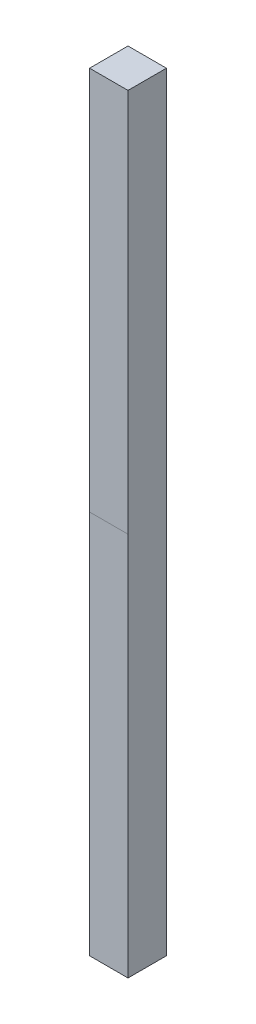
SolidWorks part; units mm, degrees
ref_plane "Front" through (0, 0, 0) normal (0, 0, 1) x (1, 0, 0)
ref_plane "Top" through (0, 0, 0) normal (0, 1, 0) x (1, 0, 0)
ref_plane "Right" through (0, 0, 0) normal (1, 0, 0) x (0, 0, -1)
other "Configuration Table"
sketch "Sketch1" plane through (0, 0, 0) normal (0, 1, 0) x (1, 0, 0)
  line L1 (0, 0) -> (25.4, 0)
  line L2 (0, 0) -> (0, 25.4)
  line L3 (0, 25.4) -> (25.4, 25.4)
  line L4 (25.4, 0) -> (25.4, 25.4)
  dimension "D1" = 25.4
  dimension "D2" = 25.4
extrude "Extrude1" add sketch "Sketch1" along normal blind 508
sketch "Sketch2" plane through (0, 0, 0) normal (0, 0, 1) x (1, 0, 0)
  line L0 (-210.197, 254) -> (255.7383, 254)
  line L1 (0, 0) -> (25.4, 0) construction
  dimension "D1" = 254
split line "Split Line1"
